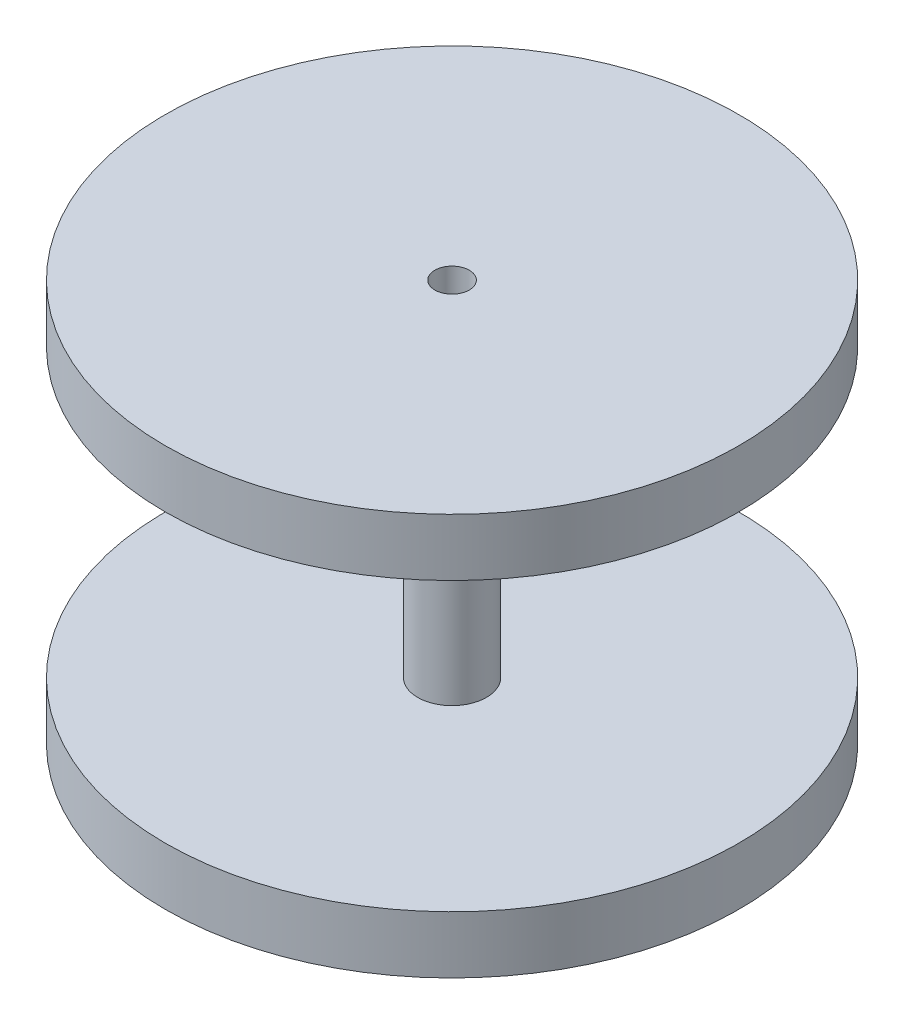
SolidWorks part; units mm, degrees
ref_plane "Front Plane" through (0, 0, 0) normal (0, 0, 1) x (1, 0, 0)
ref_plane "Top Plane" through (0, 0, 0) normal (0, 1, 0) x (1, 0, 0)
ref_plane "Right Plane" through (0, 0, 0) normal (1, 0, 0) x (0, 0, -1)
sketch "Sketch1" plane through (0, 0, 0) normal (0, 1, 0) x (1, 0, 0)
  circle A0 centre (0, 0) radius 25
extrude "Boss-Extrude1" add sketch "Sketch1" along normal blind 5
sketch "Sketch2" plane through (0, 5, 0) normal (0, 1, 0) x (1, 0, 0)
  circle A0 centre (0, 0) radius 3
extrude "Boss-Extrude2" add sketch "Sketch2" along normal blind 25
sketch "Sketch3" plane through (0, 30, 0) normal (0, 1, 0) x (1, 0, 0)
  circle A0 centre (0, 0) radius 25
extrude "Boss-Extrude3" add sketch "Sketch3" along normal blind 5 contours A0
sketch "Sketch4" plane through (0, 35, 0) normal (0, 1, 0) x (1, 0, 0)
  circle A0 centre (0, 0) radius 1.5
extrude "Cut-Extrude1" cut sketch "Sketch4" against normal through all
